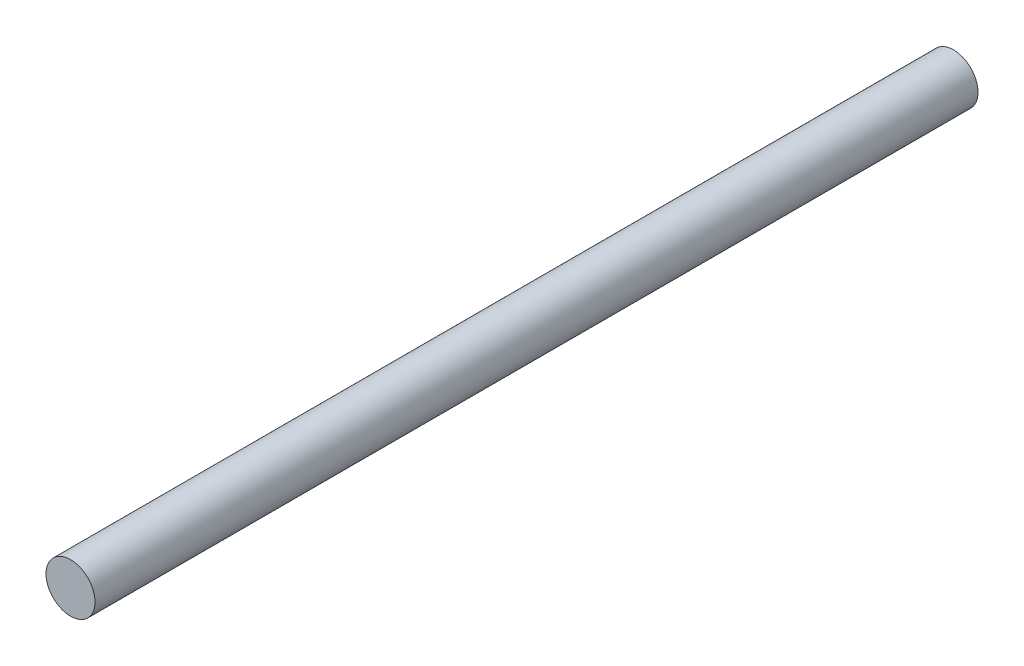
SolidWorks part; units mm, degrees
ref_plane "Front Plane" through (0, 0, 0) normal (0, 0, 1) x (1, 0, 0)
ref_plane "Top Plane" through (0, 0, 0) normal (0, 1, 0) x (1, 0, 0)
ref_plane "Right Plane" through (0, 0, 0) normal (1, 0, 0) x (0, 0, -1)
sketch "Sketch1" plane through (0, 0, 0) normal (0, 0, 1) x (1, 0, 0)
  circle A0 centre (0, 0) radius 12.7
extrude "Boss-Extrude1" add sketch "Sketch1" along normal blind 457.2
